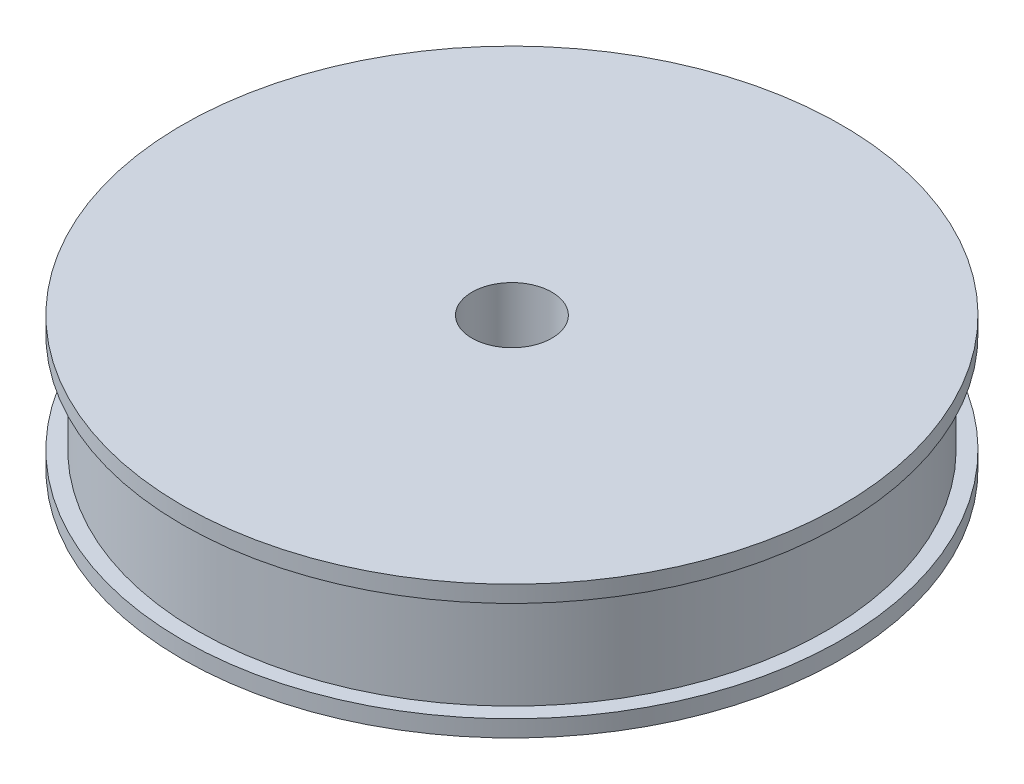
SolidWorks part; units mm, degrees
material "Lega 1060"
ref_plane "Piano frontale" through (0, 0, 0) normal (0, 0, 1) x (1, 0, 0)
ref_plane "Piano superiore" through (0, 0, 0) normal (0, 1, 0) x (1, 0, 0)
ref_plane "Piano destro" through (0, 0, 0) normal (1, 0, 0) x (0, 0, -1)
sketch "Schizzo1" plane through (0, 0, 0) normal (0, 0, 1) x (1, 0, 0)
  line L0 (0, 12.3387) -> (0, -16.129) construction
  line L1 (6, -7.6613) -> (49.5, -7.6613)
  line L2 (49.5, -7.6613) -> (49.5, -5.1613)
  line L3 (49.5, -5.1613) -> (47.175, -5.1613)
  line L4 (47.175, -5.1613) -> (47.175, 9.8387)
  line L5 (47.175, 9.8387) -> (49.5, 9.8387)
  line L6 (49.5, 9.8387) -> (49.5, 12.3387)
  line L7 (49.5, 12.3387) -> (6, 12.3387)
  line L8 (6, 12.3387) -> (6, -7.6613)
  dimension "D1" = 20
  dimension "D2" = 15
  dimension "D3" = 6
  dimension "D4" = 49.5
  dimension "D5" = 47.175
revolve "Rivoluzione1" add sketch "Schizzo1" angle 360 about L0
